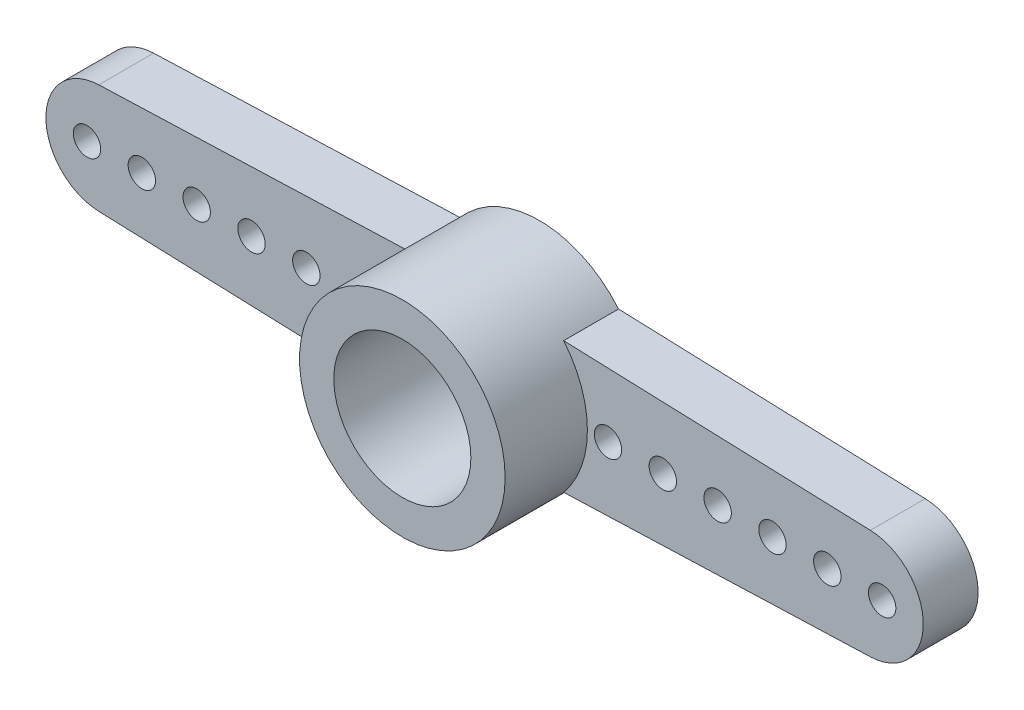
SolidWorks part; units mm, degrees
ref_plane "Спереди" through (0, 0, 0) normal (0, 0, 1) x (1, 0, 0)
ref_plane "Meio" through (0, 0, 0) normal (0, 1, 0) x (1, 0, 0)
ref_plane "Справа" through (0, 0, 0) normal (1, 0, 0) x (0, 0, -1)
sketch "Эскиз1" plane through (0, 0, 0) normal (0, 0, 1) x (1, 0, 0)
  line L0 (0, 0) -> (-14, 0)
  line L1 (-14.0708, 1.9987) -> (0, 2.4974)
  line L2 (-14.0708, -1.9987) -> (0, -2.4974)
  line L4 (14.0708, -1.9987) -> (0, -2.4974)
  line L5 (14.0708, 1.9987) -> (0, 2.4974)
  circle A0 centre (0, 0) radius 3.75
  circle A1 centre (0, 0) radius 2.5
  arc A2 (-13.967, -1.9997) -> (-14.0708, 1.9987) centre (-14, 0) cw
  arc A3 (13.967, -1.9997) -> (14.0708, 1.9987) centre (14, 0) ccw
  dimension "D1" = 7.5
  dimension "D2" = 5
  dimension "D4" = 2
  dimension "D3" = 14
extrude "Бобышка-Вытянуть3" add sketch "Эскиз1" along normal blind 2
sketch "Эскиз2" plane through (0, 0, 2) normal (0, 0, 1) x (1, 0, 0)
  circle A0 centre (0, 0) radius 3.75
  circle A1 centre (0, 0) radius 2.5
  dimension "D1" = 5
extrude "Бобышка-Вытянуть5" add sketch "Эскиз2" along normal blind 3 separate body
sketch "Эскиз3" plane through (0, 0, 2) normal (0, 0, -1) x (-1, 0, 0)
  circle A0 centre (0, 0) radius 3.75
  circle A1 centre (0, 0) radius 2.5
extrude "Бобышка-Вытянуть6" add sketch "Эскиз3" along normal blind 2
sketch "Эскиз4" plane through (0, 0, 0) normal (0, 0, -1) x (-1, 0, 0)
  line L0 (-16, 0) -> (-14.5, 0)
  line L1 (-14.5, 0) -> (-12.5, 0)
  line L2 (-12.5, 0) -> (-10.5, 0)
  line L3 (-10.5, 0) -> (-8.5, 0)
  line L4 (-8.5, 0) -> (-6.5, 0)
  line L5 (-6.5, 0) -> (-4.5, 0)
  arc A0 (-14.0708, 1.9987) -> (-14.0708, -1.9987) centre (-14, 0) ccw construction
  circle A1 centre (-14.5, 0) radius 0.5
  circle A2 centre (-12.5, 0) radius 0.5
  circle A3 centre (-10.5, 0) radius 0.5
  circle A4 centre (-8.5, 0) radius 0.5
  circle A5 centre (-6.5, 0) radius 0.5
  circle A6 centre (-4.5, 0) radius 0.5
  circle A7 centre (4.5, 0) radius 0.5
  circle A8 centre (6.5, 0) radius 0.5
  circle A9 centre (8.5, 0) radius 0.5
  circle A10 centre (10.5, 0) radius 0.5
  circle A11 centre (12.5, 0) radius 0.5
  circle A12 centre (14.5, 0) radius 0.5
  dimension "D2" = 1
  dimension "D8" = 1
  dimension "D9" = 1
  dimension "D10" = 1
  dimension "D11" = 1
  dimension "D12" = 1
  dimension "D1" = 1.5
  dimension "D3" = 2
  dimension "D4" = 2
  dimension "D5" = 2
  dimension "D6" = 2
  dimension "D7" = 2
extrude "Вырез-Вытянуть1" cut sketch "Эскиз4" against normal blind 2
sketch "Эскиз5" plane through (0, 0, 0) normal (0, 0, -1) x (-1, 0, 0)
  circle A0 centre (0, 0) radius 2.5
extrude "Бобышка-Вытянуть7" add sketch "Эскиз5" against normal blind 1
sketch "Эскиз6" plane through (0, 0, 0) normal (0, 0, -1) x (-1, 0, 0)
  circle A0 centre (0, 0) radius 2.5
  dimension "D1" = 5
extrude "Вырез-Вытянуть2" cut sketch "Эскиз6" against normal blind 0.5
sketch "Эскиз7" plane through (0, 0, 0.5) normal (0, 0, -1) x (-1, 0, 0)
  circle A0 centre (0, 0) radius 1.25
  dimension "D1" = 2.5
extrude "Вырез-Вытянуть3" cut sketch "Эскиз7" against normal blind 5
sketch "Эскиз8" plane through (0, 0, 0.5) normal (0, 0, -1) x (-1, 0, 0)
  line L0 (-2.8252, -0.1999) -> (-2.8894, -0.2509)
move or copy body "Body-Move/Copy1" [suppressed] bodies to move or copy 113
